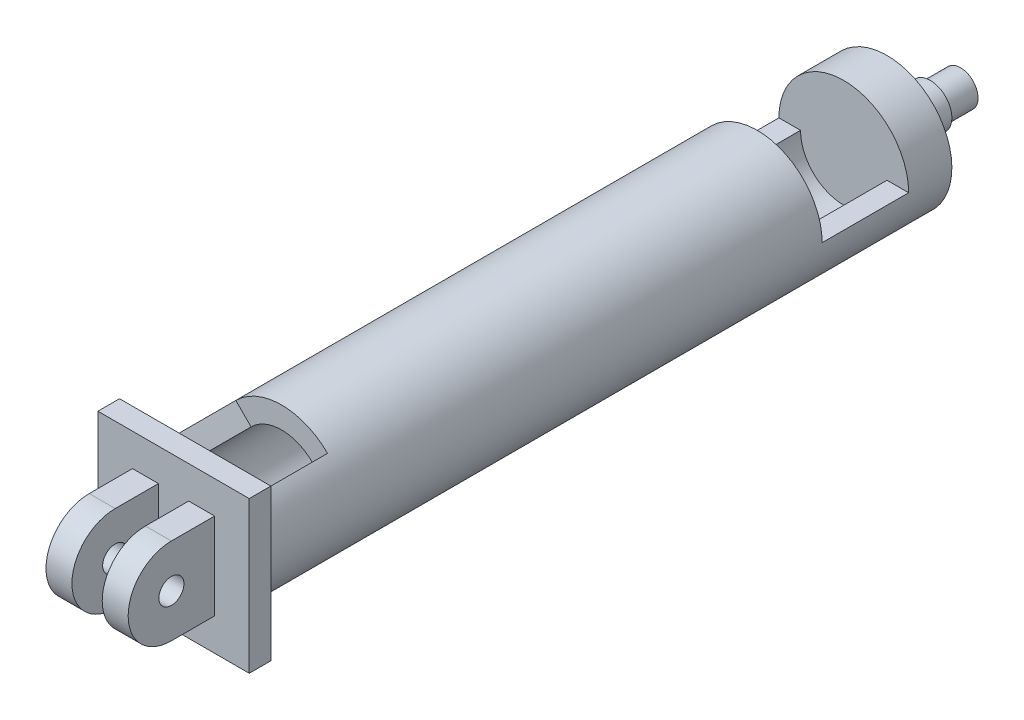
SolidWorks part; units mm, degrees
ref_plane "Front Plane" through (0, 0, 0) normal (0, 0, 1) x (1, 0, 0)
ref_plane "Top Plane" through (0, 0, 0) normal (0, 1, 0) x (1, 0, 0)
ref_plane "Right Plane" through (0, 0, 0) normal (1, 0, 0) x (0, 0, -1)
sketch "Sketch1" plane through (0, 0, 0) normal (0, 0, 1) x (1, 0, 0)
  circle A0 centre (0, 0) radius 15
  circle A1 centre (0, 0) radius 10
  dimension "D1" = 30
  dimension "D2" = 20
extrude "Boss-Extrude1" add sketch "Sketch1" along normal blind 150
sketch "Sketch2" plane through (0, 0, 150) normal (0, 0, 1) x (1, 0, 0)
  line L1 (-17.5, -17.5) -> (17.5, -17.5)
  line L2 (-17.5, -17.5) -> (-17.5, 17.5)
  line L3 (-17.5, 17.5) -> (17.5, 17.5)
  line L4 (17.5, -17.5) -> (17.5, 17.5)
  line L5 (-17.5, -17.5) -> (17.5, 17.5) construction
  line L6 (-17.5, 17.5) -> (17.5, -17.5) construction
  point P0 (0, 0)
  dimension "D1" = 35
  dimension "D2" = 35
extrude "Boss-Extrude2" add sketch "Sketch2" along normal blind 5
ref_plane "Plane1" through (3.5, 0, 0) normal (1, 0, 0) x (0, 0, -1)
ref_plane "Plane2" through (-3.5, 0, 0) normal (1, 0, 0) x (0, 0, -1)
sketch "Sketch10" plane through (0, 0, 0) normal (0, 0, -1) x (-1, 0, 0)
  line L0 (15, 0) -> (-15, 0)
  circle A0 centre (0, 0) radius 15 construction
  circle A1 centre (0, 0) radius 15
  circle M2 centre (0, 0) radius 15
  circle M3 centre (0, 0) radius 10
extrude "Cut-Extrude5" cut sketch "Sketch10" against normal blind 20 contours L0 M2 M3
sketch "Sketch12" plane through (0, 0, 0) normal (0, 0, -1) x (-1, 0, 0)
  circle A0 centre (0, 0) radius 15 construction
  circle A1 centre (0, 0) radius 15
extrude "Boss-Extrude4" add sketch "Sketch12" along normal blind 10
sketch "Sketch13" plane through (0, 0, -10) normal (0, 0, -1) x (-1, 0, 0)
  circle A0 centre (0, 0) radius 5
  dimension "D1" = 10
extrude "Boss-Extrude5" add sketch "Sketch13" along normal blind 10
sketch "Sketch14" plane through (0, 0, 150) normal (0, 0, -1) x (-1, 0, 0)
  line L0 (-15, 0) -> (15, 0)
  line L1 (0, 0) -> (-10.6066, 10.6066)
  line L2 (0, 0) -> (10.6066, 10.6066)
  circle A0 centre (0, 0) radius 15 construction
  circle A1 centre (0, 0) radius 15
  circle M1 centre (0, 0) radius 15
  dimension "D1" = 90
  dimension "D2" = 45
extrude "Cut-Extrude6" cut sketch "Sketch14" along normal blind 20 contours L0 M1
sketch "Sketch15" plane through (0, 0, -20) normal (0, 0, -1) x (-1, 0, 0)
  circle A0 centre (0, 0) radius 4.05
  dimension "D1" = 8.1
extrude "Boss-Extrude6" add sketch "Sketch15" along normal blind 7
sketch "Sketch16" plane through (-17.5, 0, 0) normal (-1, 0, 0) x (0, 0, 1)
  line L0 (155, 10) -> (165, 10)
  line L1 (155, 17.5) -> (155, -17.5) construction
  line L2 (155, 10) -> (155, -10)
  line L3 (155, -10) -> (165, -10)
  arc A0 (165, -10) -> (165, 10) centre (165, 0) ccw
  circle A1 centre (165, 0) radius 2.9
  point P5 (155, 0)
  point P7 (155, 0)
  dimension "D2" = 10
  dimension "D3" = 5.8
  dimension "D1" = 20
  dimension "D4" = 10
extrude "Boss-Extrude7" add sketch "Sketch16" against normal up to surface (35 mm away) up to face at (17.5, 0, 152.5)
sketch "Sketch17" plane through (0, 0, 155) normal (0, 0, 1) x (1, 0, 0)
  line L0 (17.5, 17.5) -> (-17.5, 17.5)
  line L1 (-17.5, 17.5) -> (-17.5, -17.5)
  line L2 (-17.5, -17.5) -> (17.5, -17.5)
  line L3 (17.5, -17.5) -> (17.5, 17.5)
  line L4 (-3.5, 17.5) -> (-3.5, -17.5)
  line L5 (-9.5, 17.5) -> (-9.5, -17.5)
  line L6 (3.5, -17.5) -> (3.5, 17.5)
  line L7 (9.5, -17.5) -> (9.5, 17.5)
  line M9 (-17.5, 10) -> (17.5, 10)
  line M10 (17.5, 10) -> (17.5, 17.5)
  line M11 (17.5, 17.5) -> (-17.5, 17.5)
  line M12 (-17.5, 17.5) -> (-17.5, 10)
  dimension "D1" = 6
  dimension "D2" = 8
  dimension "D3" = 6
  dimension "D4" = 8
extrude "Cut-Extrude7" cut sketch "Sketch17" along normal through all contours L5 L1 L2 M9 | L5 M11 M12 M9 | L6 L0 L4 M9 | L2 L6 L4 M9 | L7 M9 M10 M11 | L7 L2 L3 M9
sketch "Sketch20" plane through (0, 0, -10) normal (0, 0, -1) x (-1, 0, 0)
  line L0 (-1.5, -13.4164) -> (-1.5, -15)
  line L1 (-1.5, -15) -> (1.5, -15)
  line L2 (1.5, -15) -> (1.5, -13.4164)
  line L3 (0, -13.5) -> (0, -15) construction
  circle A0 centre (0, 0) radius 13.5
  point P7 (0, -15)
  circle M5 centre (0, 0) radius 15
  dimension "D1" = 27
  dimension "D2" = 3
  dimension "D3" = 1.5
extrude "Cut-Extrude11" cut sketch "Sketch20" against normal blind 50 contours A0 L3 L2 M5 | L3 A0 L0 M5
sketch "Sketch23" plane through (0, 0, 40) normal (0, 0, -1) x (-1, 0, 0)
  line L0 (-1.5, -13.4164) -> (-1.5, -14.9248) construction
  line L1 (-1.5, -13.4164) -> (-1.5, -14.9248)
  line L2 (-7.7433, -11.0586) -> (-8.6036, -12.2873)
  arc A0 (-10.6066, 10.6066) -> (10.6066, 10.6066) centre (0, 0) ccw construction
  arc A1 (-10.6066, 10.6066) -> (10.6066, 10.6066) centre (0, 0) ccw
  circle A2 centre (0, 0) radius 13.5
  line M4 (-1.5, -13.4164) -> (-1.5, -14.9248)
  dimension "D1" = 35
extrude "Cut-Extrude13" cut sketch "Sketch23" along normal blind 3 contours A2 L2 A1 M4
equation "\"D3@Sketch17\"=\"D1@Sketch17\""
equation "\"D4@Sketch17\"=\"D2@Sketch17\""
